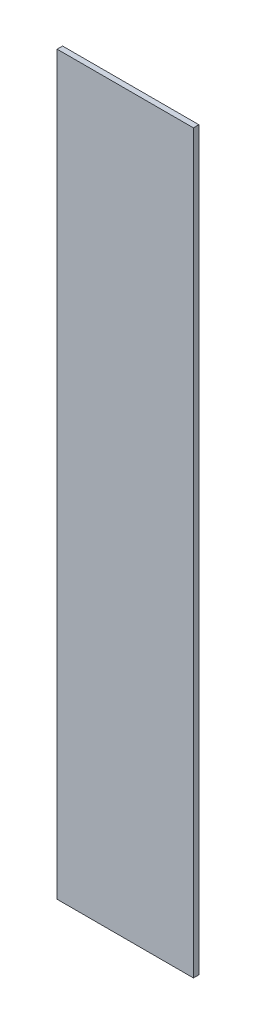
SolidWorks part; units mm, degrees
material "Бук"
ref_plane "Спереди" through (0, 0, 0) normal (0, 0, 1) x (1, 0, 0)
ref_plane "Сверху" through (0, 0, 0) normal (0, 1, 0) x (1, 0, 0)
ref_plane "Справа" through (0, 0, 0) normal (1, 0, 0) x (0, 0, -1)
sketch "Эскиз1" plane through (0, 0, 0) normal (0, 0, 1) x (1, 0, 0)
  line L1 (0, 0) -> (250, 0)
  line L2 (0, 0) -> (0, 1350)
  line L3 (0, 1350) -> (250, 1350)
  line L4 (250, 0) -> (250, 1350)
  dimension "D1" = 250
  dimension "D2" = 1350
extrude "Бобышка-Вытянуть1" add sketch "Эскиз1" along normal blind 10
